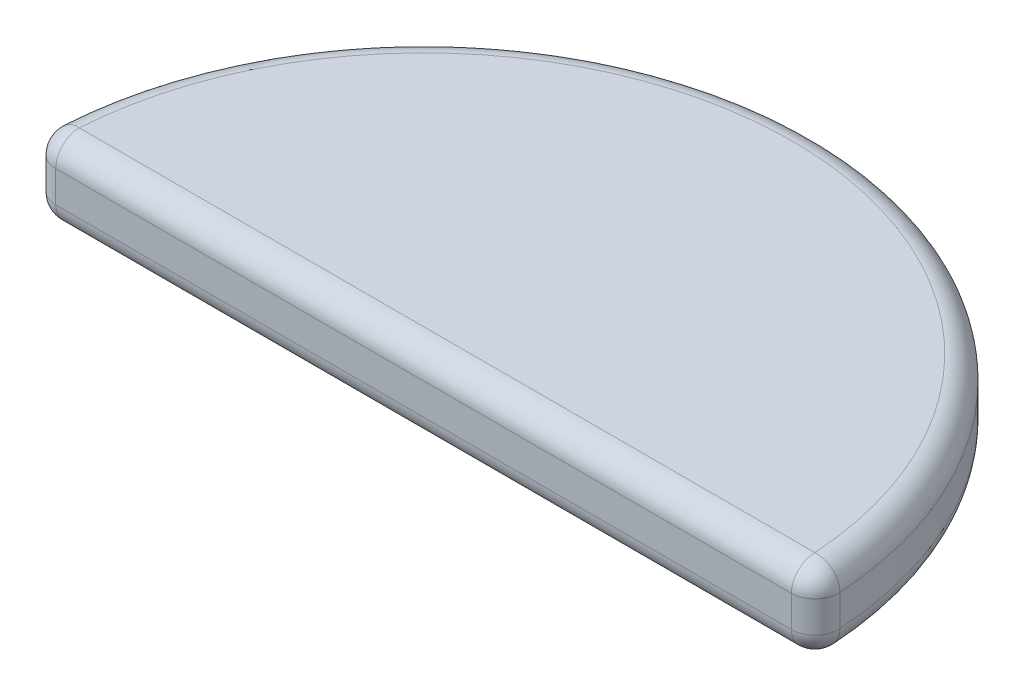
SolidWorks part; units mm, degrees
ref_plane "Front Plane" through (0, 0, 0) normal (0, 0, 1) x (1, 0, 0)
ref_plane "Top Plane" through (0, 0, 0) normal (0, 1, 0) x (1, 0, 0)
ref_plane "Right Plane" through (0, 0, 0) normal (1, 0, 0) x (0, 0, -1)
sketch "Sketch1" plane through (0, 0, 0) normal (0, 1, 0) x (1, 0, 0)
  line L0 (0, 0) -> (1000, 0)
  arc A0 (0, 0) -> (1000, 0) centre (500, 0) cw
  dimension "D1" = 500
extrude "Boss-Extrude1" add sketch "Sketch1" along normal blind 100
fillet "Fillet1" radius 30 6 edges at (500, 0, -500) (1000, 50, 0) (0, 50, 0) (500, 0, 0) (500, 100, 0) (500, 100, -500)
